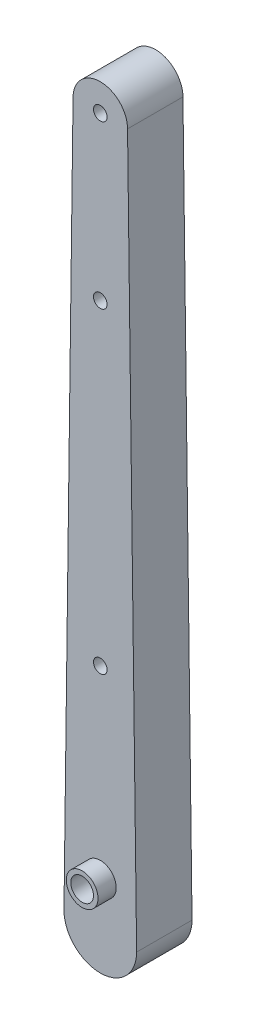
SolidWorks part; units mm, degrees
ref_plane "Front Plane" through (0, 0, 0) normal (0, 0, 1) x (1, 0, 0)
ref_plane "Top Plane" through (0, 0, 0) normal (0, 1, 0) x (1, 0, 0)
ref_plane "Right Plane" through (0, 0, 0) normal (1, 0, 0) x (0, 0, -1)
sketch "Sketch1" plane through (0, 0, 0) normal (0, 0, 1) x (1, 0, 0)
  line L0 (0, 78) -> (0, -78) construction
  line L1 (6, 78) -> (8, -78)
  line L2 (-6, 78) -> (-8, -78)
  arc A1 (-8, -78) -> (8, -78) centre (0, -78) ccw
  circle A2 centre (0, 78) radius 1.5
  circle A3 centre (0, -68) radius 2.5
  arc A4 (6, 78) -> (-6, 78) centre (0, 78) ccw
  point P3 (0, 0)
  point P8 (0, -86)
  point P9 (0, 84)
  dimension "D1" = 8
  dimension "D3" = 3
  dimension "D4" = 5
  dimension "D2" = 6
  dimension "D6" = 170
  dimension "D5" = 18
extrude "Boss-Extrude2" add sketch "Sketch1" along normal blind 12.2
sketch "Sketch3" plane through (0, 0, 12.2) normal (0, 0, 1) x (1, 0, 0)
  circle A0 centre (0, -68) radius 2.5 construction
  circle A1 centre (0, -68) radius 2.5
extrude "Extrude-Thin1" add sketch "Sketch3" along normal blind 4 separate body thin
sketch "Sketch4" plane through (0, 0, 0) normal (0, 0, -1) x (-1, 0, 0)
  circle A0 centre (0, 42.2628) radius 1.5
  circle A1 centre (0, -27.4212) radius 1.5
  dimension "D1" = 3
  dimension "D2" = 3
extrude "Cut-Extrude1" cut sketch "Sketch4" against normal blind 20
